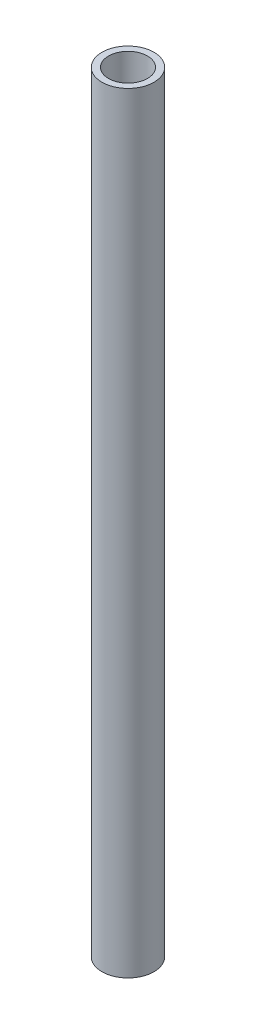
SolidWorks part; units mm, degrees
ref_plane "Front Plane" through (0, 0, 0) normal (0, 0, 1) x (1, 0, 0)
ref_plane "Top Plane" through (0, 0, 0) normal (0, 1, 0) x (1, 0, 0)
ref_plane "Right Plane" through (0, 0, 0) normal (1, 0, 0) x (0, 0, -1)
sketch "Sketch1" plane through (0, 0, 0) normal (0, 1, 0) x (1, 0, 0)
  circle A0 centre (0, 0) radius 4
  circle A1 centre (0, 0) radius 3
  dimension "D1" = 6
  dimension "D2" = 8
extrude "Boss-Extrude1" add sketch "Sketch1" along normal mid plane 118.5155
